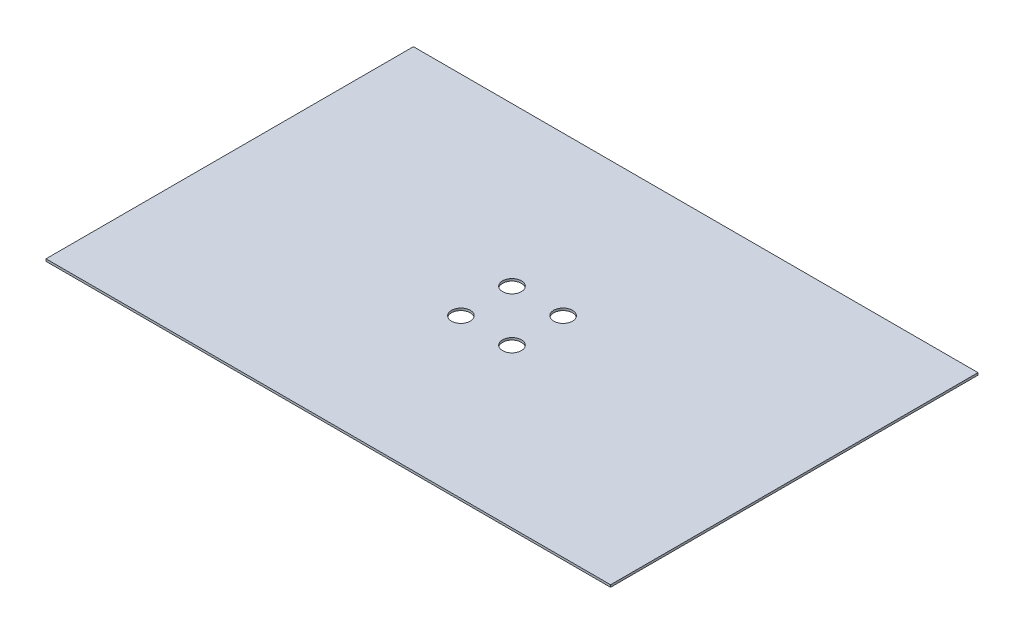
SolidWorks part; units mm, degrees
ref_plane "Front Plane" through (0, 0, 0) normal (0, 0, 1) x (1, 0, 0)
ref_plane "Top Plane" through (0, 0, 0) normal (0, 1, 0) x (1, 0, 0)
ref_plane "Right Plane" through (0, 0, 0) normal (1, 0, 0) x (0, 0, -1)
sketch "Sketch1" plane through (0, 0, 0) normal (0, 1, 0) x (1, 0, 0)
  line L1 (-630, 410) -> (630, 410)
  line L2 (-630, 410) -> (-630, -410)
  line L3 (-630, -410) -> (630, -410)
  line L4 (630, 410) -> (630, -410)
  line L5 (-630, 410) -> (630, -410) construction
  line L6 (-630, -410) -> (630, 410) construction
  circle A0 centre (-57, 57) radius 21
  circle A1 centre (57, 57) radius 21
  circle A2 centre (57, -57) radius 21
  circle A3 centre (-57, -57) radius 21
  point P0 (0, 0)
  dimension "D3" = 42
  dimension "D1" = 1260
  dimension "D2" = 820
  dimension "D4" = 57
  dimension "D5" = 57
  dimension "D6" = 2
  dimension "D7" = 2
extrude "Boss-Extrude1" add sketch "Sketch1" along normal blind 5
